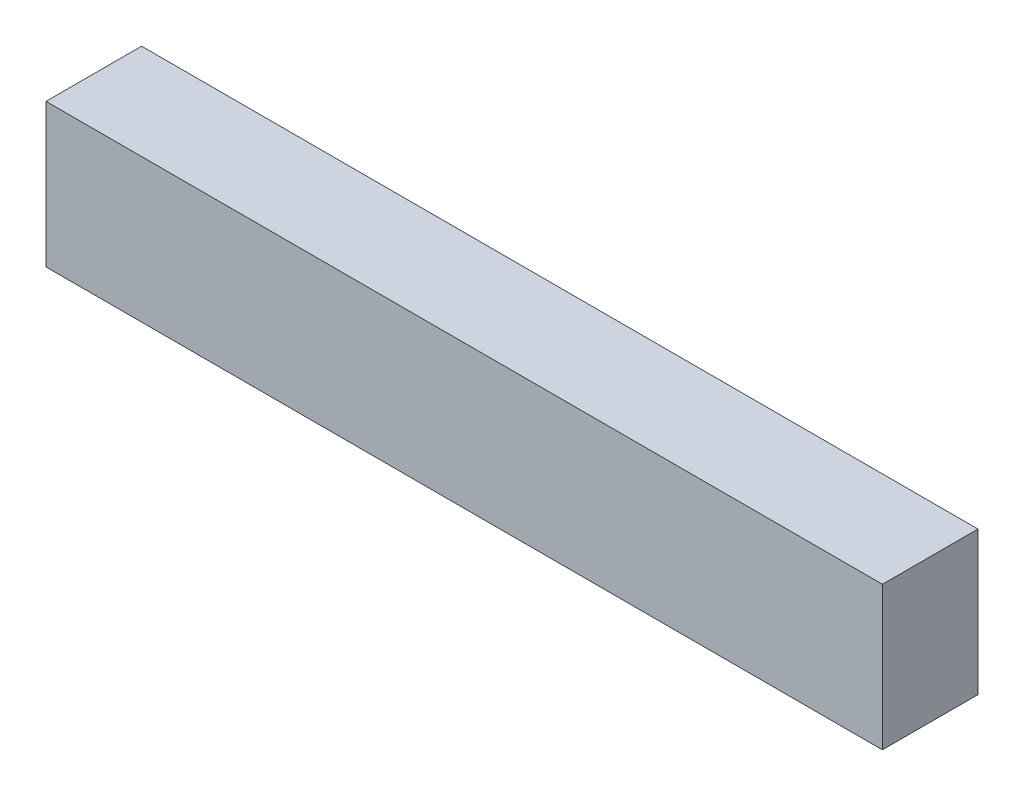
SolidWorks part; units mm, degrees
material "6061-T6 (SS)"
ref_plane "前视基准面" through (0, 0, 0) normal (0, 0, 1) x (1, 0, 0)
ref_plane "上视基准面" through (0, 0, 0) normal (0, 1, 0) x (1, 0, 0)
ref_plane "右视基准面" through (0, 0, 0) normal (1, 0, 0) x (0, 0, -1)
other "Configuration Table"
sketch "草图8" plane through (0, 0, 0) normal (0, 0, 1) x (1, 0, 0)
  line L1 (-175, 30) -> (175, 30)
  line L2 (-175, 30) -> (-175, -30)
  line L3 (-175, -30) -> (175, -30)
  line L4 (175, 30) -> (175, -30)
extrude "凸台-拉伸1" add sketch "草图8" along normal blind 40
